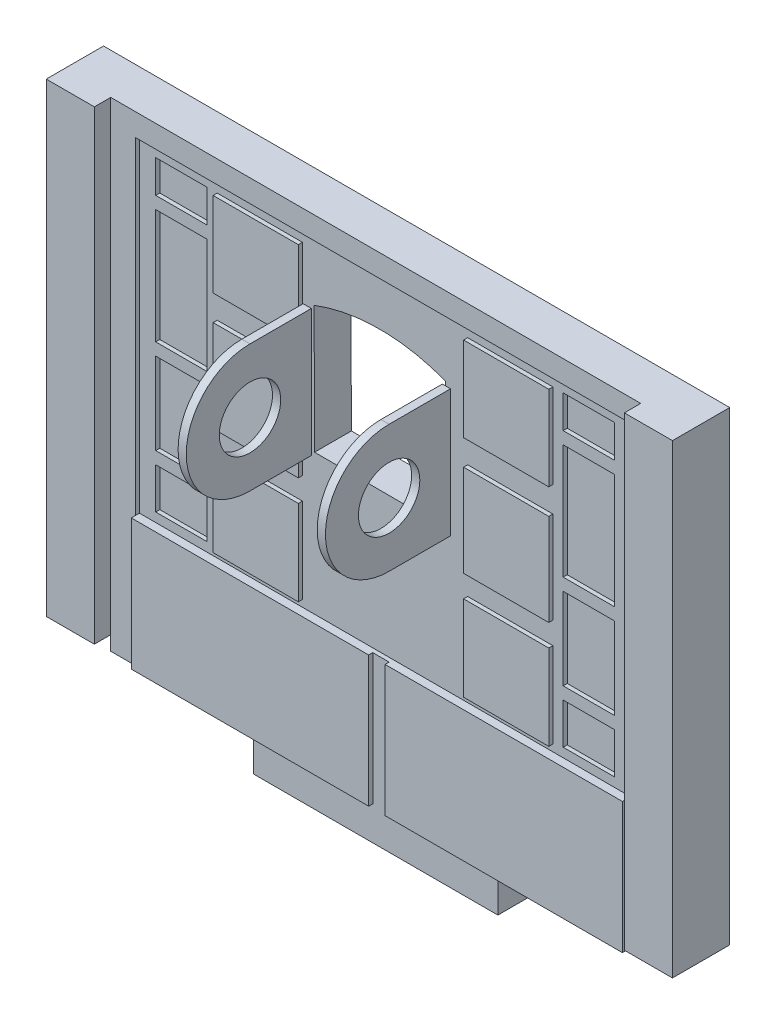
SolidWorks part; units mm, degrees
ref_plane "Front Plane" through (0, 0, 0) normal (0, 0, 1) x (1, 0, 0)
ref_plane "Top Plane" through (0, 0, 0) normal (0, 1, 0) x (1, 0, 0)
ref_plane "Right Plane" through (0, 0, 0) normal (1, 0, 0) x (0, 0, -1)
sketch "Sketch1" plane through (0, 0, 0) normal (0, 0, 1) x (1, 0, 0)
  line L0 (-66.0241, -56.3698) -> (-77.7741, -56.3698)
  line L1 (-77.7741, -56.3698) -> (-77.7741, 78.0302)
  line L2 (-77.7741, 78.0302) -> (75.2259, 78.0302)
  line L3 (75.2259, 78.0302) -> (75.2259, -56.3698)
  line L4 (75.2259, -56.3698) -> (63.4759, -56.3698)
  line L5 (63.4759, -56.3698) -> (63.4759, -39.1698)
  line L6 (63.4759, -39.1698) -> (28.5759, -39.1698)
  line L7 (28.5759, -39.1698) -> (28.5759, -47.6999)
  line L8 (28.5759, -47.6999) -> (-31.1241, -47.6999)
  line L9 (-31.1241, -47.6999) -> (-31.1241, -39.1698)
  line L10 (-31.1241, -39.1698) -> (-66.0241, -39.1698)
  line L11 (-66.0241, -39.1698) -> (-66.0241, -56.3698)
extrude "Boss-Extrude1" add sketch "Sketch1" along normal blind 10
sketch "Sketch2" plane through (0, 0, 10) normal (0, 0, 1) x (1, 0, 0)
  line L0 (75.2259, 78.0302) -> (63.4759, 78.0302)
  line L1 (75.2259, 78.0302) -> (-77.7741, 78.0302) construction
  line L2 (63.4759, 78.0302) -> (63.4759, -56.3698)
  line L3 (63.4759, -56.3698) -> (75.2259, -56.3698)
  line L4 (75.2259, -56.3698) -> (75.2259, 78.0302)
  line L5 (-66.0241, -56.3698) -> (-77.7741, -56.3698)
  line L6 (-77.7741, -56.3698) -> (-77.7741, 78.0302)
  line L7 (-77.7741, 78.0302) -> (-66.0241, 78.0302)
  line L8 (-66.0241, 78.0302) -> (-66.0241, -56.3698)
sketch "Sketch3" plane through (0, 0, 10) normal (0, 0, 1) x (1, 0, 0)
  line L0 (-17.2186, 26.8552) -> (14.7814, 26.765)
  line L1 (14.7814, 26.765) -> (14.7814, 57.8856)
  line L2 (-17.3297, 57.8856) -> (-17.2186, 26.8552)
  line L6 (-77.7741, 15.9287) -> (75.2259, 15.9287) construction
  line L7 (75.2259, -56.3698) -> (75.2259, 78.0302) construction
  arc A0 (14.7814, 57.8856) -> (-17.3297, 57.8856) centre (-1.2741, 15.9287) ccw
  point P15 (-1.2741, 15.9287)
extrude "Cut-Extrude1" cut sketch "Sketch3" against normal blind 60
ref_plane "Plane1" through (15, 0, 0) normal (1, 0, 0) x (0, 0, -1)
sketch "Sketch8" plane through (15, 0, 0) normal (1, 0, 0) x (0, 0, -1)
  line L0 (-10, 26.765) -> (-10, 57.8856)
  line L1 (-10, 57.8856) -> (-25, 57.8856)
  line L2 (-10, 26.765) -> (-25, 26.765)
  arc A0 (-25, 26.765) -> (-25, 57.8856) centre (-25, 42.3253) cw
  circle A1 centre (-25, 42.3253) radius 7.5
extrude "Boss-Extrude4" add sketch "Sketch8" along normal blind 2
ref_plane "Plane2" through (-17, 0, 0) normal (1, 0, 0) x (0, 0, -1)
sketch "Sketch9" plane through (-17, 0, 0) normal (1, 0, 0) x (0, 0, -1)
  line L0 (-10, 57.8856) -> (-25, 57.8856)
  line L1 (-10, 57.8856) -> (-10, 26.765)
  line L2 (-10, 26.765) -> (-25, 26.765)
  arc A0 (-25, 26.765) -> (-25, 57.8856) centre (-25, 42.3253) cw
  circle A1 centre (-25, 42.3253) radius 7.5
extrude "Boss-Extrude5" add sketch "Sketch9" against normal blind 2
extrude "Boss-Extrude6" add sketch "Sketch2" along normal blind 4
sketch "Sketch11" plane through (0, 0, 10) normal (0, 0, 1) x (1, 0, 0)
  line L0 (-66.0241, 78.0302) -> (-56.0241, 78.0302) construction
  line L1 (63.4759, 78.0302) -> (-66.0241, 78.0302) construction
  line L2 (-56.0241, 78.0302) -> (-56.0241, 69.7921) construction
  line L3 (-56.0241, 61.7921) -> (-56.0241, 58.7921) construction
  line L4 (-56.0241, 69.7921) -> (-43.5241, 69.7921)
  line L5 (-56.0241, 69.7921) -> (-56.0241, 61.7921)
  line L6 (-56.0241, 61.7921) -> (-43.5241, 61.7921)
  line L7 (-43.5241, 69.7921) -> (-43.5241, 61.7921)
  line L8 (-56.0241, 69.7921) -> (-43.5241, 61.7921) construction
  line L9 (-56.0241, 61.7921) -> (-43.5241, 69.7921) construction
  line L10 (-56.0241, 30.7921) -> (-56.0241, 27.7921) construction
  line L11 (-56.0241, 58.7921) -> (-43.5241, 58.7921)
  line L12 (-56.0241, 58.7921) -> (-56.0241, 30.7921)
  line L13 (-56.0241, 30.7921) -> (-43.5241, 30.7921)
  line L14 (-43.5241, 58.7921) -> (-43.5241, 30.7921)
  line L15 (-56.0241, 58.7921) -> (-43.5241, 30.7921) construction
  line L16 (-56.0241, 30.7921) -> (-43.5241, 58.7921) construction
  line L17 (-56.0241, 7.7921) -> (-56.0241, 4.7921) construction
  line L18 (-56.0241, 27.7921) -> (-43.5241, 27.7921)
  line L19 (-56.0241, 27.7921) -> (-56.0241, 7.7921)
  line L20 (-56.0241, 7.7921) -> (-43.5241, 7.7921)
  line L21 (-43.5241, 27.7921) -> (-43.5241, 7.7921)
  line L22 (-56.0241, 27.7921) -> (-43.5241, 7.7921) construction
  line L23 (-56.0241, 7.7921) -> (-43.5241, 27.7921) construction
  line L24 (0, -22.3082) -> (0, 22.3082) construction
  line L25 (-56.0241, 4.7921) -> (-43.5241, 4.7921)
  line L26 (-56.0241, 4.7921) -> (-56.0241, -5.2079)
  line L27 (-56.0241, -5.2079) -> (-43.5241, -5.2079)
  line L28 (-43.5241, 4.7921) -> (-43.5241, -5.2079)
  line L29 (-56.0241, 4.7921) -> (-43.5241, -5.2079) construction
  line L30 (-56.0241, -5.2079) -> (-43.5241, 4.7921) construction
  line L31 (56.0241, -5.2079) -> (43.5241, 4.7921) construction
  line L32 (56.0241, 4.7921) -> (43.5241, -5.2079) construction
  line L33 (56.0241, 7.7921) -> (43.5241, 27.7921) construction
  line L34 (56.0241, 27.7921) -> (43.5241, 7.7921) construction
  line L35 (56.0241, 7.7921) -> (56.0241, 4.7921) construction
  line L36 (56.0241, 30.7921) -> (43.5241, 58.7921) construction
  line L37 (56.0241, 58.7921) -> (43.5241, 30.7921) construction
  line L38 (56.0241, 30.7921) -> (56.0241, 27.7921) construction
  line L39 (56.0241, 61.7921) -> (43.5241, 69.7921) construction
  line L40 (56.0241, 69.7921) -> (43.5241, 61.7921) construction
  line L41 (56.0241, 61.7921) -> (56.0241, 58.7921) construction
  line L42 (56.0241, 78.0302) -> (56.0241, 69.7921) construction
  line L43 (66.0241, 78.0302) -> (56.0241, 78.0302) construction
  line L44 (43.5241, 4.7921) -> (43.5241, -5.2079)
  line L45 (56.0241, -5.2079) -> (43.5241, -5.2079)
  line L46 (56.0241, 4.7921) -> (56.0241, -5.2079)
  line L47 (56.0241, 4.7921) -> (43.5241, 4.7921)
  line L48 (43.5241, 27.7921) -> (43.5241, 7.7921)
  line L49 (56.0241, 7.7921) -> (43.5241, 7.7921)
  line L50 (56.0241, 27.7921) -> (56.0241, 7.7921)
  line L51 (56.0241, 27.7921) -> (43.5241, 27.7921)
  line L52 (43.5241, 58.7921) -> (43.5241, 30.7921)
  line L53 (56.0241, 30.7921) -> (43.5241, 30.7921)
  line L54 (56.0241, 58.7921) -> (56.0241, 30.7921)
  line L55 (56.0241, 58.7921) -> (43.5241, 58.7921)
  line L56 (43.5241, 69.7921) -> (43.5241, 61.7921)
  line L57 (56.0241, 61.7921) -> (43.5241, 61.7921)
  line L58 (56.0241, 69.7921) -> (56.0241, 61.7921)
  line L59 (56.0241, 69.7921) -> (43.5241, 69.7921)
  point P9 (-49.7741, 65.7921)
  point P14 (-49.7741, 44.7921)
  point P19 (-49.7741, 17.7921)
  point P24 (-49.7741, -0.2079)
  point P45 (49.7741, -0.2079)
  point P46 (49.7741, 17.7921)
  point P47 (49.7741, 44.7921)
  point P48 (49.7741, 65.7921)
  dimension "D1" = 12.5
  dimension "D2" = 8
  dimension "D3" = 28
  dimension "D4" = 20
  dimension "D5" = 10
extrude "Cut-Extrude2" cut sketch "Sketch11" against normal blind 2
sketch "Sketch12" plane through (0, 0, 10) normal (0, 0, 1) x (1, 0, 0)
  line L1 (-60, 72.5626) -> (60, 72.5626)
  line L2 (-60, 72.5626) -> (-60, -7.4374)
  line L3 (-60, -7.4374) -> (60, -7.4374)
  line L4 (60, 72.5626) -> (60, -7.4374)
  line L5 (-60, 72.5626) -> (60, -7.4374) construction
  line L6 (-60, -7.4374) -> (60, 72.5626) construction
  point P4 (0, 32.5626)
  dimension "D1" = 120
  dimension "D2" = 80
extrude "Cut-Extrude4" cut sketch "Sketch12" against normal blind 1
sketch "Sketch14" plane through (0, 0, 9) normal (0, 0, 1) x (1, 0, 0)
  line L0 (0, -22.3082) -> (0, 22.3082) construction
  line L1 (-41.0076, 69.7921) -> (-20.1882, 69.7921)
  line L2 (-41.0076, 69.7921) -> (-41.0076, 49.1375)
  line L3 (-41.0076, 49.1375) -> (-20.1882, 49.1375)
  line L4 (-20.1882, 69.7921) -> (-20.1882, 49.1375)
  line L5 (-41.0076, 69.7921) -> (-20.1882, 49.1375) construction
  line L6 (-41.0076, 49.1375) -> (-20.1882, 69.7921) construction
  line L7 (-41.0076, 42.8917) -> (-20.1882, 42.8917)
  line L8 (-41.0076, 42.8917) -> (-41.0076, 20.4286)
  line L9 (-41.0076, 20.4286) -> (-20.1882, 20.4286)
  line L10 (-20.1882, 42.8917) -> (-20.1882, 20.4286)
  line L11 (-41.0076, 42.8917) -> (-20.1882, 20.4286) construction
  line L12 (-41.0076, 20.4286) -> (-20.1882, 42.8917) construction
  line L13 (-41.0076, 15.0326) -> (-20.1882, 15.0326)
  line L14 (-41.0076, 15.0326) -> (-41.0076, -5.7858)
  line L15 (-41.0076, -5.7858) -> (-20.1882, -5.7858)
  line L16 (-20.1882, 15.0326) -> (-20.1882, -5.7858)
  line L17 (-41.0076, 15.0326) -> (-20.1882, -5.7858) construction
  line L18 (-41.0076, -5.7858) -> (-20.1882, 15.0326) construction
  line L19 (41.0076, 20.4286) -> (20.1882, 42.8917) construction
  line L20 (41.0076, 42.8917) -> (20.1882, 20.4286) construction
  line L21 (41.0076, 49.1375) -> (20.1882, 69.7921) construction
  line L22 (41.0076, 69.7921) -> (20.1882, 49.1375) construction
  line L23 (20.1882, 42.8917) -> (20.1882, 20.4286)
  line L24 (41.0076, 20.4286) -> (20.1882, 20.4286)
  line L25 (41.0076, 42.8917) -> (41.0076, 20.4286)
  line L26 (41.0076, 42.8917) -> (20.1882, 42.8917)
  line L27 (20.1882, 69.7921) -> (20.1882, 49.1375)
  line L28 (41.0076, 49.1375) -> (20.1882, 49.1375)
  line L29 (41.0076, 69.7921) -> (41.0076, 49.1375)
  line L30 (41.0076, 69.7921) -> (20.1882, 69.7921)
  line L31 (41.0076, -5.7858) -> (20.1882, -5.7858)
  line L32 (20.1882, 15.0326) -> (20.1882, -5.7858)
  line L33 (41.0076, 15.0326) -> (20.1882, 15.0326)
  line L34 (41.0076, 15.0326) -> (41.0076, -5.7858)
  line L35 (41.0076, -5.7858) -> (20.1882, 15.0326) construction
  line L36 (41.0076, 15.0326) -> (20.1882, -5.7858) construction
  point P4 (-30.5979, 59.4648)
  point P9 (-30.5979, 31.6601)
  point P14 (-30.5979, 4.6234)
  point P25 (30.5979, 31.6601)
  point P26 (30.5979, 59.4648)
  point P31 (30.5979, 4.6234)
extrude "Boss-Extrude7" add sketch "Sketch14" along normal blind 1
sketch "Sketch15" plane through (0, 0, 10) normal (0, 0, 1) x (1, 0, 0)
  line L1 (-60, -7.4374) -> (-2, -7.4374)
  line L2 (-60, -7.4374) -> (-60, -39.4374)
  line L3 (-60, -39.4374) -> (-2, -39.4374)
  line L4 (-2, -7.4374) -> (-2, -39.4374)
  line L5 (-60, -7.4374) -> (-2, -39.4374) construction
  line L6 (-60, -39.4374) -> (-2, -7.4374) construction
  line L7 (60, -7.4374) -> (2, -7.4374)
  line L8 (60, -7.4374) -> (60, -39.4374)
  line L9 (60, -39.4374) -> (2, -39.4374)
  line L10 (2, -7.4374) -> (2, -39.4374)
  line L11 (60, -7.4374) -> (2, -39.4374) construction
  line L12 (60, -39.4374) -> (2, -7.4374) construction
  point P4 (-31, -23.4374)
  point P9 (31, -23.4374)
  dimension "D1" = 58
  dimension "D3" = 58
extrude "Boss-Extrude8" add sketch "Sketch15" along normal blind 1
sketch "Sketch16" plane through (0, 0, 14) normal (0, 0, 1) x (1, 0, 0)
  line L0 (-77.7741, 78.0302) -> (-77.7741, -56.3698) construction
  line L1 (-77.7741, -35.6811) -> (-66.0241, -35.6811)
  line L2 (-77.7741, -35.6811) -> (-77.7741, -56.3698)
  line L3 (-77.7741, -56.3698) -> (-66.0241, -56.3698)
  line L4 (-66.0241, -35.6811) -> (-66.0241, -56.3698)
  line L5 (-77.7741, -35.6811) -> (-66.0241, -56.3698) construction
  line L6 (-77.7741, -56.3698) -> (-66.0241, -35.6811) construction
  line L7 (63.4759, 78.0302) -> (63.4759, -56.3698) construction
  line L8 (63.4759, -35.6811) -> (75.2259, -35.6811)
  line L9 (63.4759, -35.6811) -> (63.4759, -56.3698)
  line L10 (63.4759, -56.3698) -> (75.2259, -56.3698)
  line L11 (75.2259, -35.6811) -> (75.2259, -56.3698)
  line L12 (63.4759, -35.6811) -> (75.2259, -56.3698) construction
  line L13 (63.4759, -56.3698) -> (75.2259, -35.6811) construction
  point P4 (-71.8991, -46.0255)
  point P12 (69.3509, -46.0255)
extrude "Cut-Extrude5" cut sketch "Sketch16" against normal blind 30
